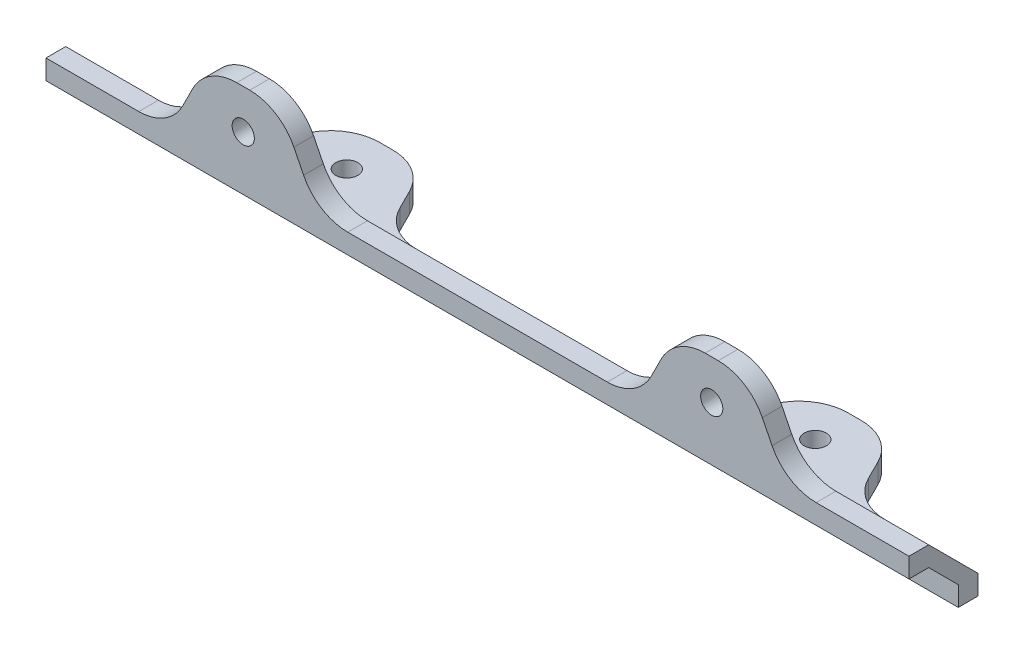
SolidWorks part; units mm, degrees
ref_plane "Piano frontale" through (0, 0, 0) normal (0, 0, 1) x (1, 0, 0)
ref_plane "Piano superiore" through (0, 0, 0) normal (0, 1, 0) x (1, 0, 0)
ref_plane "Piano destro" through (0, 0, 0) normal (1, 0, 0) x (0, 0, -1)
sketch "Schizzo3" plane through (0, 0, 0) normal (1, 0, 0) x (0, 0, -1)
  line L0 (0, 0) -> (4, 0)
  line L1 (4, 0) -> (-6, 10)
  line L2 (-6, 10) -> (-6, 6)
  line L3 (-6, 6) -> (0, 0)
  dimension "D1" = 4
  dimension "D2" = 10
extrude "Estrusione-Estrusione1" add sketch "Schizzo3" along normal blind 175
sketch "Schizzo4" plane through (0, 0, 0) normal (0, -1, 0) x (1, 0, 0)
  line L0 (25, -4) -> (32.5, -19)
  line L1 (175, -4) -> (0, -4) construction
  line L2 (32.5, -19) -> (47.5, -19)
  line L3 (47.5, -19) -> (55, -4)
  line L4 (55, -4) -> (25, -4) construction
  line L5 (120, -4) -> (127.5, -19)
  line L6 (127.5, -19) -> (142.5, -19)
  line L7 (142.5, -19) -> (150, -4)
  line L8 (120, -4) -> (150, -4) construction
  line L9 (25, -4) -> (0, -4)
  line L10 (0, -4) -> (0, 0)
  line L11 (0, 0) -> (175, 0)
  line L12 (175, 0) -> (175, -4)
  line L13 (175, -4) -> (150, -4)
  line L14 (120, -4) -> (55, -4)
  dimension "D1" = 30
  dimension "D2" = 15
  dimension "D3" = 25
  dimension "D4" = 25
  dimension "D5" = 15
extrude "Estrusione-Estrusione2" add sketch "Schizzo4" along normal blind 4
sketch "Schizzo5" plane through (0, 0, 6) normal (0, 0, 1) x (1, 0, 0)
  line L0 (0, 6) -> (0, 10)
  line L1 (0, 10) -> (25, 10)
  line L2 (175, 10) -> (0, 10) construction
  line L3 (25, 10) -> (32.5, 25)
  line L4 (32.5, 25) -> (47.5, 25)
  line L5 (47.5, 25) -> (55, 10)
  line L6 (55, 10) -> (120, 10)
  line L7 (120, 10) -> (127.5, 25)
  line L8 (127.5, 25) -> (142.5, 25)
  line L9 (142.5, 25) -> (150, 10)
  line L10 (150, 10) -> (175, 10)
  line L11 (175, 10) -> (175, 6)
  line L12 (175, 6) -> (0, 6)
  dimension "D1" = 15
  dimension "D2" = 15
  dimension "D3" = 30
  dimension "D4" = 25
extrude "Estrusione-Estrusione3" add sketch "Schizzo5" along normal blind 4
fillet "Raccordo1" radius 10 16 edges at (150, -2, -4) (120, -2, -4) (55, -2, -4) (25, -2, -4) (142.5, -2, -19) (127.5, -2, -19) (47.5, -2, -19) (32.5, -2, -19) (150, 10, 8) (142.5, 25, 8) (127.5, 25, 8) (120, 10, 8) (47.5, 25, 8) (32.5, 25, 8) (25, 10, 8) (55, 10, 8)
sketch "Schizzo6" plane through (0, 0, 0) normal (0, 1, 0) x (1, 0, 0)
  line L0 (40, 4) -> (40, 11) construction
  line L1 (61.1803, 4) -> (18.8197, 4) construction
  line L3 (135, 11) -> (135, 4) construction
  line L4 (156.1803, 4) -> (113.8197, 4) construction
  point P0 (135, 11)
  point P2 (40, 11)
  dimension "D1" = 7
  dimension "D2" = 7
hole_wizard "Foro per Vite M4-1" positions "Schizzo6" profile "Schizzo7" hole size "M4" standard "ISO"
sketch "Schizzo7" plane through (135, 0, -11) normal (1, 0, 0) x (0, 0, 1)
  line L0 (0, 0) -> (0, 14.3519)
  line L1 (0, 14.3519) -> (2.25, 13)
  line L2 (2.25, 13) -> (2.25, 0)
  line L5 (2.25, 0) -> (0, 0)
  line L10 (0, 14.3519) -> (-2.25, 13) construction
  line L11 (0, -6.35) -> (0, 107.95) construction
  dimension "Hole Dia." = 4.5
  dimension "Hole Depth" = 13
  dimension "Drill Angle" = 118
hole_wizard "Foro per Vite M4-2" positions "Schizzo8" profile "Schizzo9" hole size "M4" standard "ISO"
sketch "Schizzo8" plane through (0, 0, 6) normal (0, 0, -1) x (-1, 0, 0)
  line L0 (-135, 17) -> (-135, 10) construction
  line L1 (-156.1803, 10) -> (-113.8197, 10) construction
  line L3 (-40, 17) -> (-40, 10) construction
  line L4 (-61.1803, 10) -> (-18.8197, 10) construction
  point P0 (-40, 17)
  point P2 (-135, 17)
  dimension "D1" = 7
  dimension "D2" = 7
sketch "Schizzo9" plane through (40, 17, 6) normal (1, 0, 0) x (0, 1, 0)
  line L0 (0, 0) -> (0, 14.3519)
  line L1 (0, 14.3519) -> (2.25, 13)
  line L2 (2.25, 13) -> (2.25, 0)
  line L5 (2.25, 0) -> (0, 0)
  line L10 (0, 14.3519) -> (-2.25, 13) construction
  line L11 (0, -6.35) -> (0, 107.95) construction
  dimension "Hole Dia." = 4.5
  dimension "Hole Depth" = 13
  dimension "Drill Angle" = 118
